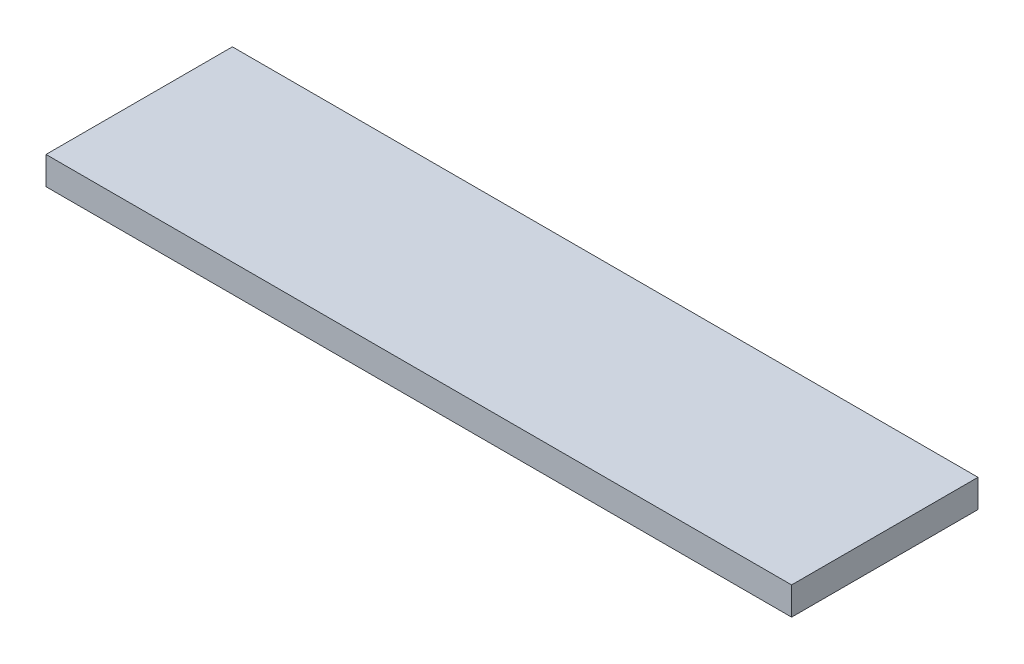
SolidWorks part; units mm, degrees
ref_plane "Front Plane" through (0, 0, 0) normal (0, 0, 1) x (1, 0, 0)
ref_plane "Top Plane" through (0, 0, 0) normal (0, 1, 0) x (1, 0, 0)
ref_plane "Right Plane" through (0, 0, 0) normal (1, 0, 0) x (0, 0, -1)
sketch "Sketch2" plane through (0, 0, 0) normal (0, 1, 0) x (1, 0, 0)
  line L1 (-31.75, 7.9375) -> (31.75, 7.9375)
  line L2 (-31.75, 7.9375) -> (-31.75, -7.9375)
  line L3 (-31.75, -7.9375) -> (31.75, -7.9375)
  line L4 (31.75, 7.9375) -> (31.75, -7.9375)
  dimension "D1" = 15.875
  dimension "D2" = 63.5
  dimension "D3" = 7.9375
  dimension "D4" = 31.75
extrude "Boss-Extrude1" add sketch "Sketch2" along normal blind 2.3813
sketch "Sketch3" plane through (0, 2.3813, 0) normal (0, 1, 0) x (1, 0, 0)
  line L0 (-31.75, 0) -> (31.75, 0) construction
  line L1 (-31.75, 7.9375) -> (-31.75, -7.9375) construction
  line L2 (31.75, -7.9375) -> (31.75, 7.9375) construction
  circle A0 centre (0, 0) radius 0.0127
  dimension "D1" = 0.0254
extrude "Cut-Extrude1" cut sketch "Sketch3" against normal up to next
